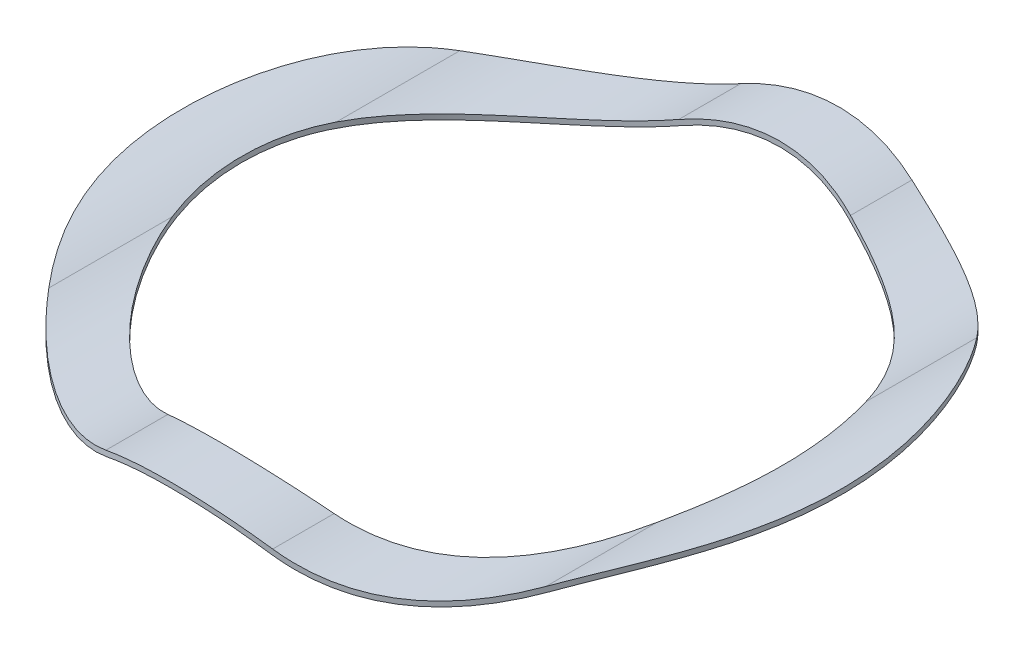
SolidWorks part; units mm, degrees
ref_plane "Plan de face" through (0, 0, 0) normal (0, 0, 1) x (1, 0, 0)
ref_plane "Plan de dessus" through (0, 0, 0) normal (0, 1, 0) x (1, 0, 0)
ref_plane "Plan de droite" through (0, 0, 0) normal (1, 0, 0) x (0, 0, -1)
sketch "Esquisse1" plane through (0, 0, 0) normal (0, 0, 1) x (1, 0, 0)
  line L0 (-27.2297, 0) -> (123.5201, 0) construction
  arc A1 (0, 0) -> (10, 0) centre (5, -12) cw
  arc A2 (10, 0) -> (20, 0) centre (15, 12) ccw
  arc A3 (20, 0) -> (30, 0) centre (25, -12) cw
  arc A4 (30, 0) -> (40, 0) centre (35, 12) ccw
  arc A5 (40, 0) -> (50, 0) centre (45, -12) cw
  dimension "D1" = 13
  dimension "D2" = 12
  dimension "D3" = 12
extrude "Extru.-Mince1" add sketch "Esquisse1" against normal blind 40 thin
ref_plane "Plan1" through (0, 5, 0) normal (0, 1, 0) x (-1, 0, 0)
sketch "Esquisse2" plane through (0, 5, 0) normal (0, 1, 0) x (-1, 0, 0)
  circle A0 centre (-25.2441, -19.8699) radius 19.5
  circle A1 centre (-25.2441, -19.8699) radius 16
  dimension "D1" = 39
  dimension "D2" = 32
extrude "Enlèv. mat.-Extru.1" cut sketch "Esquisse2" against normal blind 40 flip side to cut
